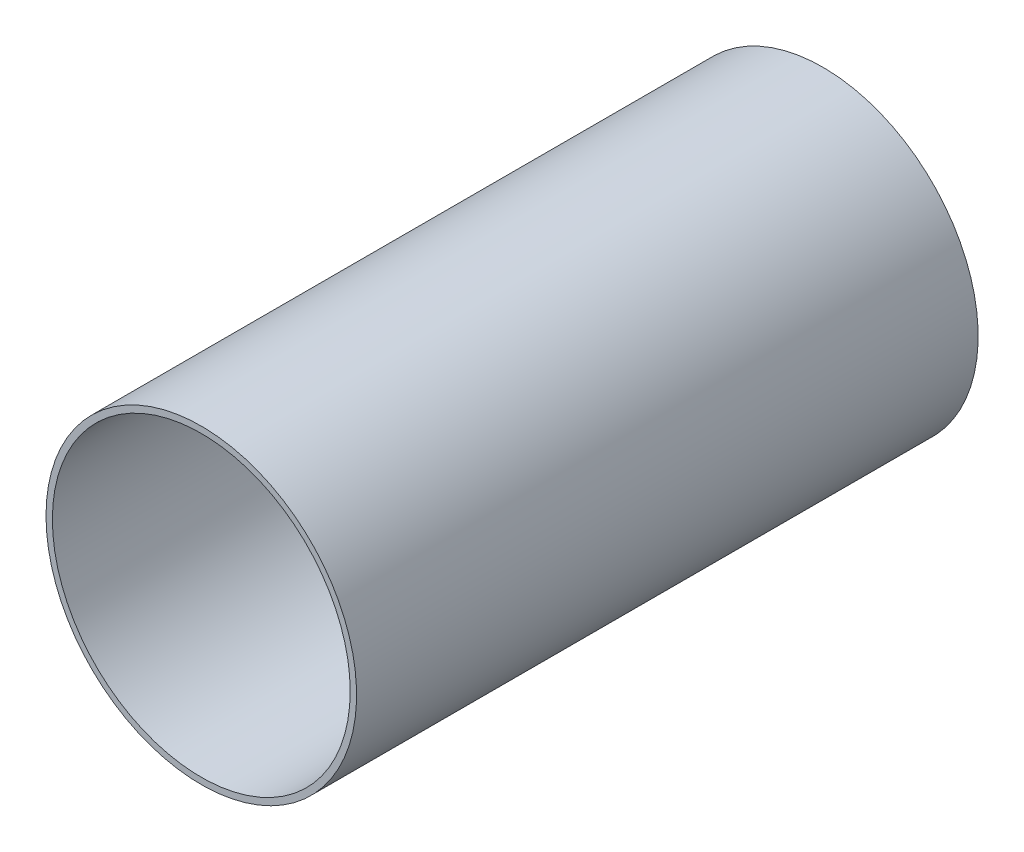
SolidWorks part; units mm, degrees
ref_plane "Front Plane" through (0, 0, 0) normal (0, 0, 1) x (1, 0, 0)
ref_plane "Top Plane" through (0, 0, 0) normal (0, 1, 0) x (1, 0, 0)
ref_plane "Right Plane" through (0, 0, 0) normal (1, 0, 0) x (0, 0, -1)
sketch "Sketch1" plane through (0, 0, 0) normal (0, 0, 1) x (1, 0, 0)
  circle A0 centre (0, 0) radius 36.5125
  circle A1 centre (0, 0) radius 38.0746
  dimension "D1" = 73.025
  dimension "D2" = 76.1492
extrude "Boss-Extrude1" add sketch "Sketch1" along normal blind 152.4
